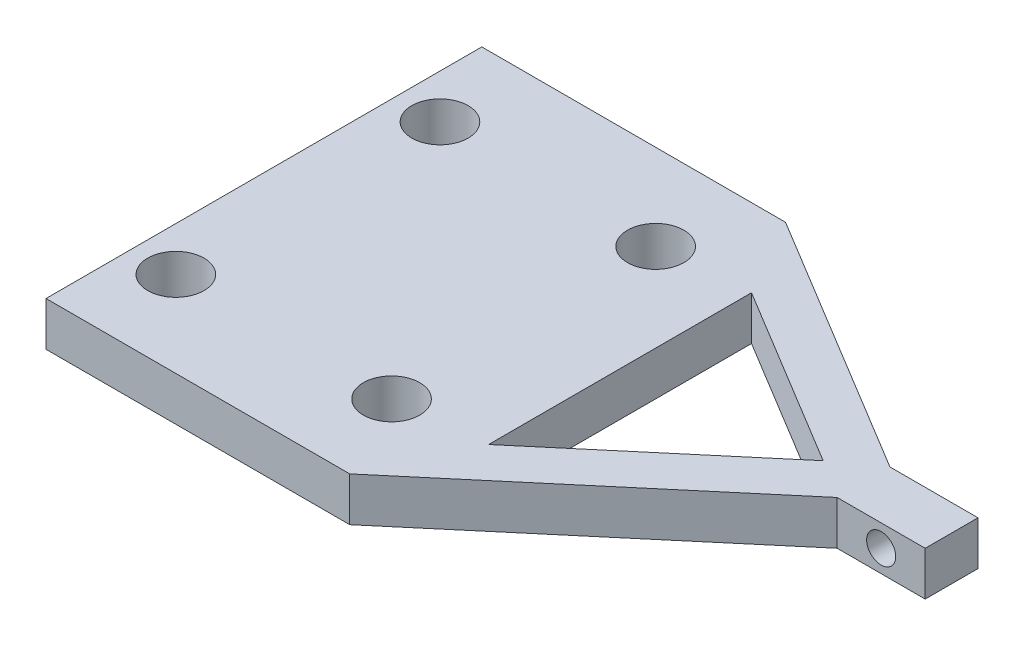
SolidWorks part; units mm, degrees
ref_plane "Front Plane" through (0, 0, 0) normal (0, 0, 1) x (1, 0, 0)
ref_plane "Top Plane" through (0, 0, 0) normal (0, 1, 0) x (1, 0, 0)
ref_plane "Right Plane" through (0, 0, 0) normal (1, 0, 0) x (0, 0, -1)
sketch "Sketch1" plane through (0, 0, 0) normal (0, 1, 0) x (1, 0, 0)
  line L1 (0, 0) -> (34.5, 0)
  line L2 (0, 0) -> (0, 49.5)
  line L3 (0, 49.5) -> (34.5, 49.5)
  line L4 (34.5, 0) -> (34.5, 49.5)
  dimension "D1" = 34.5
  dimension "D2" = 49.5
extrude "Boss-Extrude1" add sketch "Sketch1" along normal blind 5
sketch "Sketch2" plane through (0, 5, 0) normal (0, 1, 0) x (1, 0, 0)
  line L0 (34.5, 49.5) -> (0, 49.5) construction
  line L1 (0, 49.5) -> (0, 0) construction
  line L2 (17.25, 49.5) -> (17.25, 0) construction
  line L3 (0, 0) -> (34.5, 0) construction
  line L4 (0, 24.75) -> (17.25, 24.75) construction
  circle A0 centre (5, 39.75) radius 3.2
  circle A1 centre (5, 9.75) radius 3.2
  circle A2 centre (29.5, 9.75) radius 3.2
  circle A3 centre (29.5, 39.75) radius 3.2
  dimension "D1" = 6.4
  dimension "D3" = 5
  dimension "D2" = 9.75
extrude "Cut-Extrude1" cut sketch "Sketch2" against normal blind 5
sketch "Sketch3" plane through (0, 5, 0) normal (0, 1, 0) x (1, 0, 0)
  line L0 (17.25, 24.75) -> (181.75, 24.75) construction
  line L1 (189.75, 42.25) -> (34.5, 49.5)
  line L2 (189.75, 7.25) -> (34.5, 0)
  line L3 (189.75, 42.25) -> (189.75, 7.25)
  line L4 (171.0535, 14.3856) -> (89.0949, 10.5582)
  line L6 (171.0535, 35.1144) -> (89.0949, 38.9418)
  line L7 (34.5, 49.5) -> (34.5, 41.4913)
  line L8 (34.5, 0) -> (34.5, 49.5) construction
  line L9 (181.75, 34.6149) -> (34.1268, 41.5087) construction
  line L10 (34.5, 0) -> (34.5, 8.0087)
  line L11 (181.75, 14.8851) -> (34.1268, 7.9913) construction
  line L12 (84.0949, 39.1753) -> (84.0949, 10.3247)
  line L13 (89.0949, 38.9418) -> (89.0949, 10.5582)
  line L14 (89.0949, 39.1753) -> (89.0949, 10.3247) construction
  line L16 (0, 49.5) -> (0, 0) construction
  line L17 (0, 0) -> (34.5, 0) construction
  line L18 (84.0949, 39.1753) -> (34.5, 41.4913)
  line L19 (84.0949, 10.3247) -> (34.5, 8.0087)
  line L20 (171.0535, 35.1144) -> (171.0535, 14.3856)
  line L21 (181.75, 34.6149) -> (181.75, 14.8851) construction
  line L22 (178.13, 37.25) -> (184.13, 37.25)
  line L23 (178.13, 37.25) -> (178.13, 12.25)
  line L24 (178.13, 12.25) -> (184.13, 12.25)
  line L25 (184.13, 37.25) -> (184.13, 12.25)
  dimension "D1" = 17.5
  dimension "D4" = 17.25
  dimension "D5" = 24.75
  dimension "D6" = 17.5
  dimension "D7" = 172.5
  dimension "D8" = 25
  dimension "D9" = 12.5
  dimension "D10" = 6
  dimension "D11" = 5.62
  dimension "D2" = 8
  dimension "D3" = 5
extrude "Boss-Extrude2" add sketch "Sketch3" against normal blind 5
sketch "Sketch5" [suppressed] plane through (0, 5, 0) normal (0, 1, 0) x (1, 0, 0)
  line L0 (163.183, 43.1642) -> (163.183, 6.3358)
  line L1 (181.75, 42.25) -> (34.5, 49.5) construction
  line L2 (34.5, 0) -> (181.75, 7.25) construction
  line L3 (163.183, 6.3358) -> (181.75, 7.25)
  line L4 (181.75, 7.25) -> (181.75, 42.25)
  line L5 (181.75, 42.25) -> (163.183, 43.1642)
fillet "Fillet1" radius 10 6 edges at (89.0949, 2.5, -10.5582) (89.0949, 2.5, -38.9418) (84.0949, 2.5, -10.3247) (84.0949, 2.5, -39.1753) (34.5, 2.5, -41.4913) (34.5, 2.5, -8.0087)
fillet "Fillet2" radius 5 2 edges at (171.0535, 2.5, -14.3856) (171.0535, 2.5, -35.1144)
sketch "Sketch6" plane through (0, 5, 0) normal (0, 1, 0) x (1, 0, 0)
  line L1 (34.5, 49.5) -> (200.6847, 49.5)
  line L2 (34.5, 49.5) -> (34.5, 0)
  line L3 (34.5, 0) -> (200.6847, 0)
  line L4 (200.6847, 49.5) -> (200.6847, 0)
  line L5 (34.5, 49.5) -> (200.6847, 0) construction
  line L6 (34.5, 0) -> (200.6847, 49.5) construction
  point P4 (117.5923, 24.75)
extrude "Cut-Extrude3" cut sketch "Sketch6" against normal blind 10
sketch "Sketch7" plane through (0, 5, 0) normal (0, 1, 0) x (1, 0, 0)
  line L0 (64.5, 31.3606) -> (34.5, 49.5)
  line L1 (74.5, 31.3606) -> (64.5, 31.3606)
  line L2 (74.5, 31.3606) -> (74.5, 25.3606)
  line L3 (74.5, 25.3606) -> (64.5, 25.3606)
  line L5 (74.5, 31.3606) -> (64.5, 25.3606) construction
  line L6 (74.5, 25.3606) -> (64.5, 31.3606) construction
  line L7 (34.5, 49.5) -> (34.5, 0)
  line L8 (34.5, 0) -> (64.5, 25.3606)
  line L9 (64.5, 31.3606) -> (64.5, 25.3606)
  line L10 (69.5, 31.3606) -> (69.5, 25.3606)
  line L11 (60.093, 28.1823) -> (39.5, 40.6338)
  line L12 (39.5, 40.6338) -> (39.5, 10.7739)
  line L13 (39.5, 10.7739) -> (60.093, 28.1823)
  line L14 (61.9129, 27.0819) -> (39.5, 40.6338) construction
  line L15 (39.5, 10.7739) -> (61.2721, 29.179) construction
  point P4 (69.5, 28.3606)
  dimension "D1" = 6
  dimension "D3" = 30
  dimension "D4" = 10
  dimension "D2" = 5
extrude "Boss-Extrude3" add sketch "Sketch7" against normal up to surface (5 mm away) contours L11 L12 L13 | L0 L7 L8 L3 L2 L1 up to face at (17.25, 0, -24.75)
sketch "Sketch8" plane through (0, 0, -25.3606) normal (0, 0, 1) x (1, 0, 0)
  line L0 (74.5, 0) -> (74.5, 5) construction
  circle A0 centre (69.5, 2.5) radius 1.65
  dimension "D1" = 3.3
  dimension "D2" = 5
extrude "Cut-Extrude4" cut sketch "Sketch8" against normal blind 10
